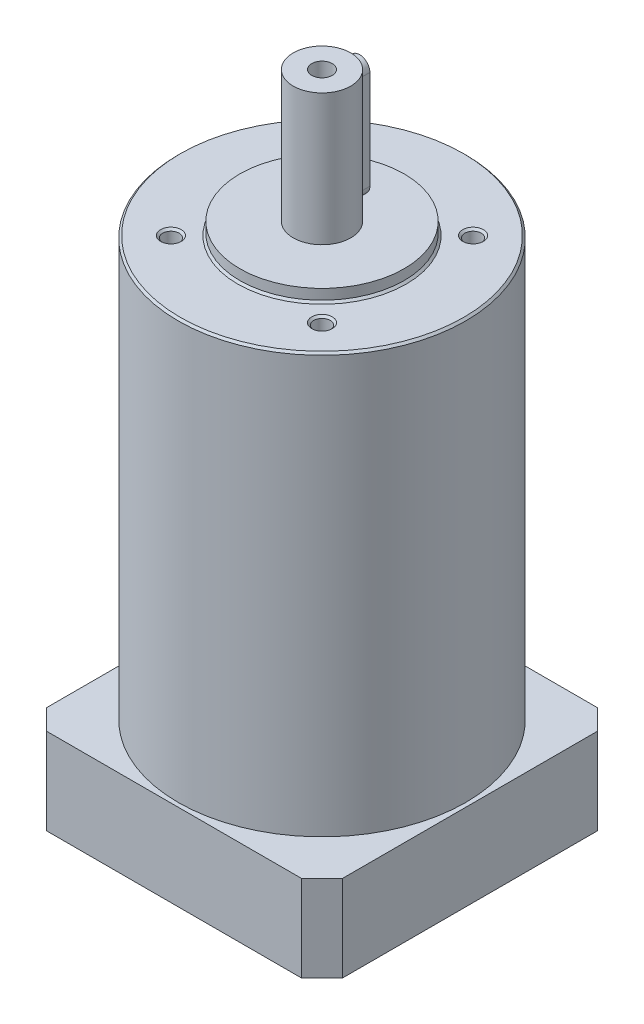
SolidWorks part; units mm, degrees
ref_plane "Front" through (0, 0, 0) normal (0, 0, 1) x (1, 0, 0)
ref_plane "Top" through (0, 0, 0) normal (0, 1, 0) x (1, 0, 0)
ref_plane "Right" through (0, 0, 0) normal (1, 0, 0) x (0, 0, -1)
sketch "Эскиз1" plane through (0, 0, 0) normal (0, 1, 0) x (1, 0, 0)
  circle A0 centre (0, 0) radius 35
  dimension "D1" = 70
extrude "Вытянуть1" add sketch "Эскиз1" along normal blind 102
sketch "Эскиз2" plane through (0, 102, 0) normal (0, 1, 0) x (1, 0, 0)
  circle A0 centre (0, 0) radius 20
extrude "Вытянуть2" add sketch "Эскиз2" along normal blind 3
sketch "Эскиз3" plane through (0, 105, 0) normal (0, 1, 0) x (1, 0, 0)
  circle A0 centre (0, 0) radius 7
extrude "Вытянуть3" add sketch "Эскиз3" along normal blind 32
sketch "Эскиз4" plane through (0, 0, 0) normal (0, -1, 0) x (1, 0, 0)
  line L1 (-36, 36) -> (36, 36)
  line L2 (-36, 36) -> (-36, -36)
  line L3 (-36, -36) -> (36, -36)
  line L4 (36, 36) -> (36, -36)
  dimension "D1" = 72
  dimension "D2" = 36
  dimension "D3" = 72
  dimension "D4" = 36
extrude "Вытянуть4" add sketch "Эскиз4" along normal blind 21
chamfer "Фаска1" distance 5 angle 45 4 edges at (-36, -10.5, -36) (36, -10.5, -36) (36, -10.5, 36) (-36, -10.5, 36)
sketch "Эскиз5" plane through (0, 102, 0) normal (0, 1, 0) x (1, 0, 0)
  line L0 (18.3848, 18.3848) -> (0, 0) construction
  line L1 (0, 0) -> (-18.3848, -18.3848) construction
  line L2 (-18.3848, -18.3848) -> (-18.3848, 18.3848) construction
  line L3 (-18.3848, 18.3848) -> (18.3848, -18.3848) construction
  line L4 (0, 0) -> (0, 26) construction
  line L5 (0, 0) -> (0, -26) construction
  line L6 (-26, 0) -> (26, 0) construction
  circle A0 centre (-18.3848, 18.3848) radius 2
  circle A1 centre (18.3848, 18.3848) radius 2
  circle A2 centre (-18.3848, -18.3848) radius 2
  circle A3 centre (18.3848, -18.3848) radius 2
  circle A4 centre (0, 0) radius 26 construction
  dimension "D3" = 2
  dimension "D4" = 2
  dimension "D1" = 52
  dimension "D5" = 4
  dimension "D2" = 45
extrude "Вырез-Вытянуть1" cut sketch "Эскиз5" against normal blind 10
chamfer "Фаска2" distance 0.5 angle 45 6 edges at (0, 102, 20) (0, 102, 35) (-18.3848, 102, -16.3848) (18.3848, 102, -16.3848) (-18.3848, 102, 20.3848) (18.3848, 102, 20.3848)
sketch "Эскиз6" plane through (0, -21, 0) normal (0, -1, 0) x (1, 0, 0)
  circle A0 centre (0, 0) radius 25
  dimension "D1" = 50
extrude "Вырез-Вытянуть2" cut sketch "Эскиз6" against normal blind 9
sketch "Эскиз7" plane through (0, -12, 0) normal (0, -1, 0) x (1, 0, 0)
  circle A0 centre (0, 0) radius 8
  dimension "D1" = 16
extrude "Вырез-Вытянуть3" cut sketch "Эскиз7" against normal blind 9
sketch "Эскиз9" plane through (0, -21, 0) normal (0, -1, 0) x (1, 0, 0)
  line L0 (-24.7487, 24.7487) -> (24.7487, -24.7487) construction
  line L1 (24.7487, -24.7487) -> (24.7487, 24.7487) construction
  line L2 (24.7487, 24.7487) -> (-24.7487, -24.7487) construction
  line L3 (0, 0) -> (0, 35) construction
  circle A0 centre (-24.7487, 24.7487) radius 2.5
  circle A1 centre (24.7487, 24.7487) radius 2.5
  circle A2 centre (-24.7487, -24.7487) radius 2.5
  circle A3 centre (24.7487, -24.7487) radius 2.5
  circle A4 centre (0, 0) radius 35 construction
  dimension "D3" = 5
  dimension "D1" = 70
  dimension "D2" = 45
  dimension "D4" = 45
  dimension "D5" = 45
  dimension "D6" = 45
extrude "Вырез-Вытянуть4" cut sketch "Эскиз9" against normal blind 9
sketch "Эскиз10" plane through (0, 137, 0) normal (0, 1, 0) x (1, 0, 0)
  circle A0 centre (0, 0) radius 2.5
  dimension "D1" = 5
extrude "Вырез-Вытянуть5" cut sketch "Эскиз10" against normal blind 19
ref_plane "Плоскость1" through (0, 0, -7.151) normal (0, 0, 1) x (1, 0, 0)
sketch "Эскиз12" plane through (0, 0, -7.151) normal (0, 0, 1) x (1, 0, 0)
  line L0 (0, 137) -> (0, 87.7318) construction
  line L1 (2.5, 137) -> (-2.5, 137) construction
  line L2 (0, 133.0563) -> (0, 109.0563) construction
  line L3 (2.5, 133.0563) -> (2.5, 109.0563)
  line L4 (-2.5, 133.0563) -> (-2.5, 109.0563)
  arc A0 (2.5, 133.0563) -> (-2.5, 133.0563) centre (0, 133.0563) ccw
  arc A1 (-2.5, 109.0563) -> (2.5, 109.0563) centre (0, 109.0563) ccw
  point P7 (0, 121.0563)
  dimension "D1" = 5
  dimension "D2" = 24
extrude "Бобышка-Вытянуть1" add sketch "Эскиз12" against normal blind 2 and the other way blind 1
sketch "Эскиз13" plane through (0, -3, 0) normal (0, -1, 0) x (1, 0, 0)
  circle A0 centre (0, 0) radius 7.4974
  circle A1 centre (0, 0) radius 6
  dimension "D1" = 12
extrude "Бобышка-Вытянуть2" add sketch "Эскиз13" along normal up to surface (9 mm away) up to face at (0, -12, -8)
sketch "Эскиз14" plane through (0, -3, 0) normal (0, -1, 0) x (1, 0, 0)
  circle A0 centre (0, 0) radius 6
extrude "Вырез-Вытянуть6" cut sketch "Эскиз14" against normal blind 19
